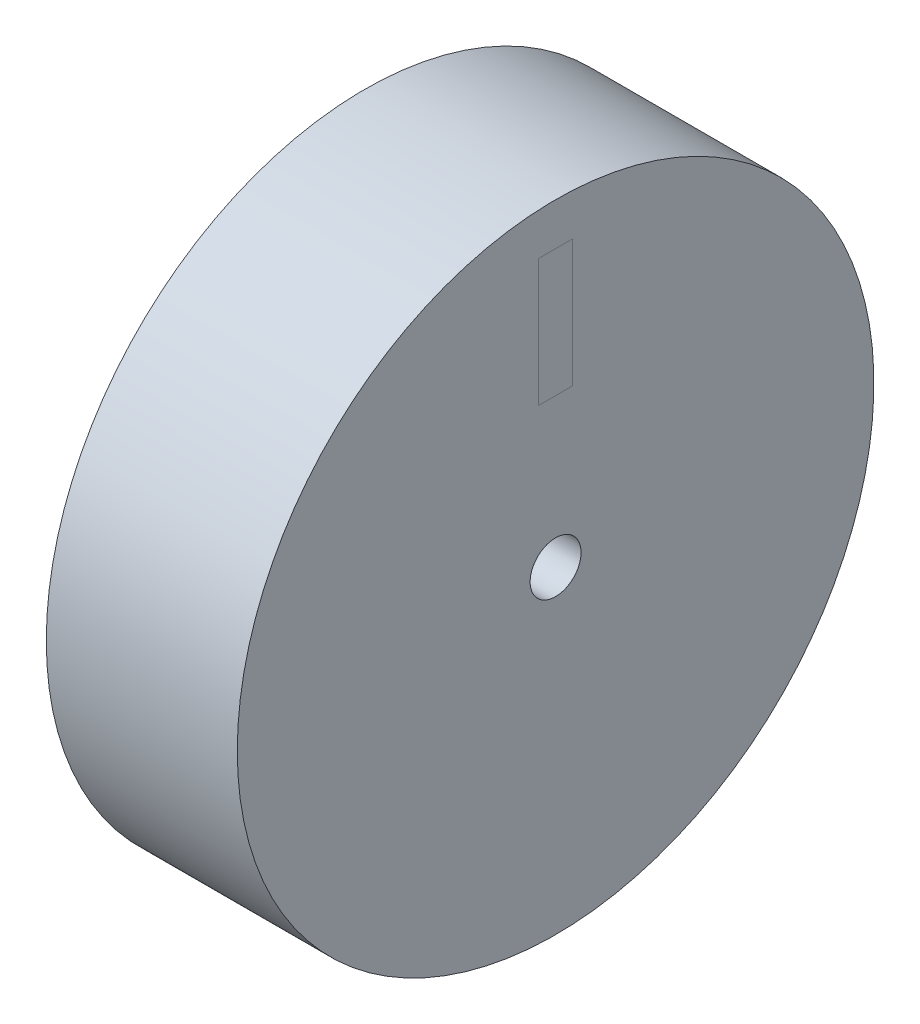
SolidWorks part; units mm, degrees
ref_plane "Front Plane" through (0, 0, 0) normal (0, 0, 1) x (1, 0, 0)
ref_plane "Top Plane" through (0, 0, 0) normal (0, 1, 0) x (1, 0, 0)
ref_plane "Right Plane" through (0, 0, 0) normal (1, 0, 0) x (0, 0, -1)
sketch "Sketch1" plane through (0, 0, 0) normal (1, 0, 0) x (0, 0, -1)
  circle A0 centre (0, 0) radius 75
  circle A1 centre (0, 0) radius 6
  dimension "D1" = 150
  dimension "D2" = 12
extrude "Boss-Extrude1" add sketch "Sketch1" along normal mid plane 45
sketch "Sketch2" plane through (22.5, 0, 0) normal (1, 0, 0) x (0, 0, -1)
  line L0 (0, 0) -> (0, 75) construction
  line L2 (-4, 35) -> (4, 35)
  line L3 (-4, 35) -> (-4, 65)
  line L4 (-4, 65) -> (4, 65)
  line L5 (4, 35) -> (4, 65)
  line L6 (-4, 35) -> (4, 65) construction
  line L7 (-4, 65) -> (4, 35) construction
  circle A0 centre (0, 0) radius 75 construction
  circle A1 centre (0, 0) radius 6 construction
  point P6 (0, 50)
  point P11 (0, 0)
  point P14 (0, 0)
  dimension "D1" = 8
  dimension "D2" = 30
  dimension "D3" = 50
split line "Split Line1"
equation "\"WheelDiameter\"= 150mm"
equation "\"WheelRadius\"= \"WheelDiameter\" / 2"
equation "\"DT_WheelWidth\"= 45mm"
equation "\"DT_Wheelbase\"= 300mm"
equation "\"DT_ShaftDiameter\"= 12mm"
equation "\"DT_FrontShaftLength\"= 180mm"
equation "\"DT_RearShaftLength\"= 200mm"
equation "\"DT_BearingWidth\"= 20mm"
equation "\"DT_BearingHousingWidth\"= 60mm"
equation "\"DT_BearingHousingHeight\"= 35mm"
equation "\"DT_ChainPitch\"= 9.525mm"
equation "\"DT_SprocketTeeth\"= 18"
equation "\"DT_SprocketPitchDiameter\"= \"DT_ChainPitch\" / sin(180deg / \"DT_SprocketTeeth\")"
equation "\"DT_SprocketOuterDiameter\"= 60mm"
equation "\"DT_SprocketThickness\"= 6mm"
equation "\"DT_SprocketHubDiameter\"= 25mm"
equation "\"DT_SprocketHubLength\"= 20mm"
equation "\"DT_CouplingDiameter\"= 30mm"
equation "\"DT_CouplingLength\"= 35mm"
equation "\"DT_MotorDiameter\"= 60mm"
equation "\"DT_MotorLength\"= 120mm"
equation "\"DT_MotorShaftDiameter\"= 8mm"
equation "\"DT_MotorShaftLength\"= 20mm"
equation "\"Stripe_Width\"= \"WheelDiameter\" * 0.0533'\"Stripe"
equation "\"Stripe_Length\"= \"WheelDiameter\" * 0.2"
equation "\"Center_Offset\"= \"WheelDiameter\" / 3"
